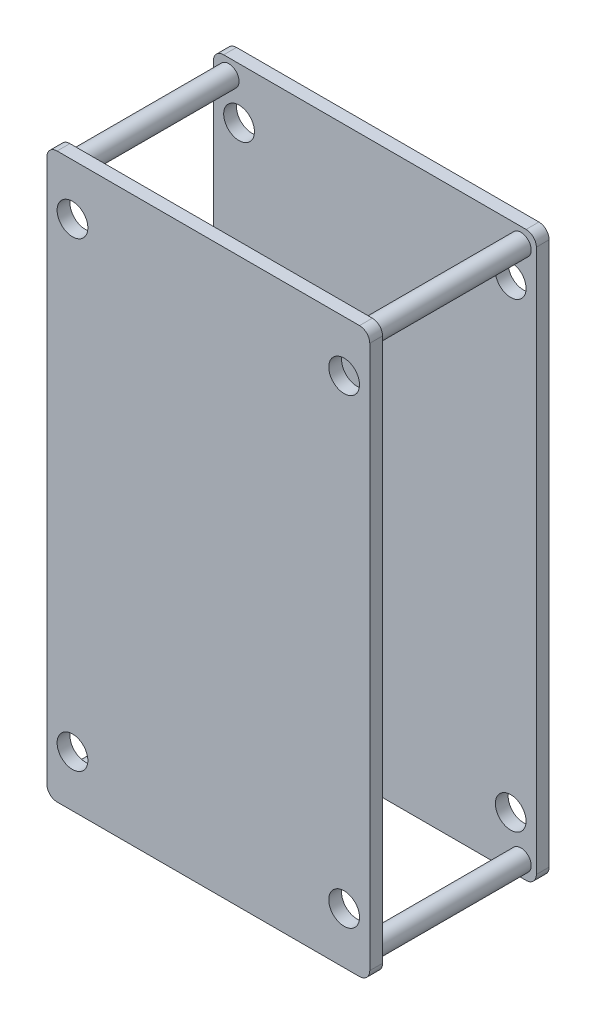
SolidWorks part; units mm, degrees
ref_plane "Front Plane" through (0, 0, 0) normal (0, 0, 1) x (1, 0, 0)
ref_plane "Top Plane" through (0, 0, 0) normal (0, 1, 0) x (1, 0, 0)
ref_plane "Right Plane" through (0, 0, 0) normal (1, 0, 0) x (0, 0, -1)
sketch "Sketch1" plane through (0, 0, 0) normal (0, 0, 1) x (1, 0, 0)
  line L1 (-31.5, -55) -> (31.5, -55)
  line L2 (-31.5, -55) -> (-31.5, 55)
  line L3 (-31.5, 55) -> (31.5, 55)
  line L4 (31.5, -55) -> (31.5, 55)
  line L5 (-31.5, -55) -> (31.5, 55) construction
  line L6 (-31.5, 55) -> (31.5, -55) construction
  circle A0 centre (-26.5, 45) radius 3
  circle A1 centre (-26.5, -45) radius 3
  circle A2 centre (26.5, -45) radius 3
  circle A3 centre (26.5, 45) radius 3
  point P0 (0, 0)
  dimension "D1" = 63
  dimension "D2" = 110
extrude "Boss-Extrude1" add sketch "Sketch1" along normal blind 2.5
sketch "Sketch3" plane through (0, 0, 2.5) normal (0, 0, 1) x (1, 0, 0)
  circle A4 centre (-28.5, 52) radius 2
  circle A5 centre (28.5, 52) radius 2
  circle A6 centre (28.5, -52) radius 2
  circle A7 centre (-28.5, -52) radius 2
extrude "Boss-Extrude3" add sketch "Sketch3" along normal blind 30
fillet "Fillet2" radius 2 1 edges at (31.5, -55, 1.25)
fillet "Fillet3" radius 2 1 edges at (31.5, 55, 1.25)
fillet "Fillet4" radius 2 1 edges at (-31.5, 55, 1.25)
fillet "Fillet5" radius 2 1 edges at (-31.5, -55, 1.25)
ref_plane "Plane1" through (0, 0, 32.5) normal (0, 0, 1) x (1, 0, 0)
sketch "Sketch5" plane through (0, 0, 32.5) normal (0, 0, 1) x (1, 0, 0)
  line L1 (-31.5, -55) -> (31.5, -55)
  line L2 (-31.5, -55) -> (-31.5, 55)
  line L3 (-31.5, 55) -> (31.5, 55)
  line L4 (31.5, -55) -> (31.5, 55)
  line L5 (-31.5, -55) -> (31.5, 55) construction
  line L6 (-31.5, 55) -> (31.5, -55) construction
  circle A0 centre (-26.5, 45) radius 3
  circle A1 centre (-26.5, -45) radius 3
  circle A2 centre (26.5, -45) radius 3
  circle A3 centre (26.5, 45) radius 3
  point P0 (0, 0)
  dimension "D1" = 63
  dimension "D2" = 110
extrude "Boss-Extrude5" add sketch "Sketch5" along normal blind 2.5
fillet "Fillet10" radius 2 1 edges at (31.5, 55, 33.75)
fillet "Fillet11" radius 2 1 edges at (31.5, -55, 33.75)
fillet "Fillet12" radius 2 1 edges at (-31.5, -55, 33.75)
fillet "Fillet13" radius 2 1 edges at (-31.5, 55, 33.75)
